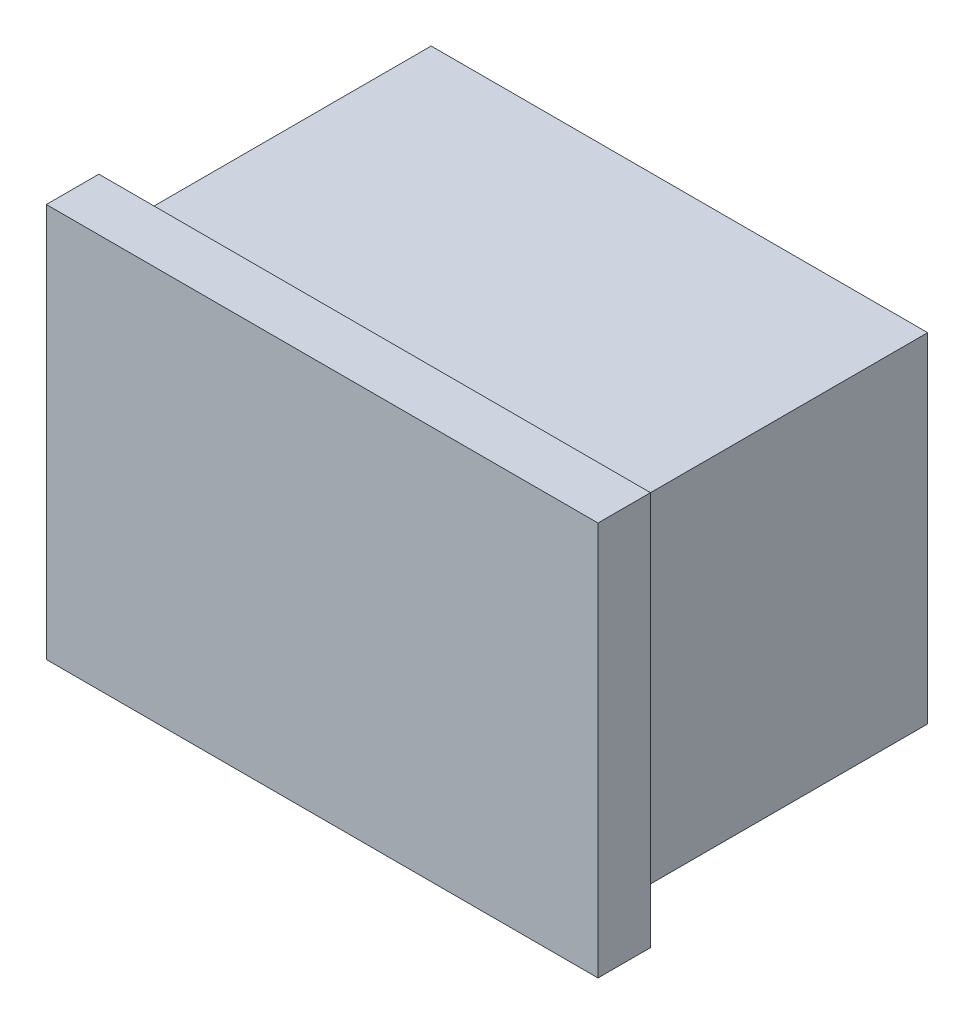
SolidWorks part; units mm, degrees
ref_plane "Front Plane" through (0, 0, 0) normal (0, 0, 1) x (1, 0, 0)
ref_plane "Top Plane" through (0, 0, 0) normal (0, 1, 0) x (1, 0, 0)
ref_plane "Right Plane" through (0, 0, 0) normal (1, 0, 0) x (0, 0, -1)
sketch "Sketch1" plane through (0, 0, 0) normal (0, 0, 1) x (1, 0, 0)
  line L1 (0, 0) -> (18.9, 0)
  line L2 (0, 0) -> (0, 12.9)
  line L3 (0, 12.9) -> (18.9, 12.9)
  line L4 (18.9, 0) -> (18.9, 12.9)
  dimension "D1" = 18.9
  dimension "D2" = 12.9
extrude "Boss-Extrude1" add sketch "Sketch1" along normal blind 11.6
sketch "Sketch2" plane through (0, 0, 11.6) normal (0, 0, 1) x (1, 0, 0)
  line L0 (18.9, 0) -> (18.9, 12.9) construction
  line L1 (19.95, 13.95) -> (-1.05, 13.95)
  line L2 (19.95, 13.95) -> (19.95, -1.05)
  line L3 (19.95, -1.05) -> (-1.05, -1.05)
  line L4 (-1.05, 13.95) -> (-1.05, -1.05)
  line L5 (0, 0) -> (18.9, 0) construction
  point P4 (19.95, 6.45)
  point P7 (18.9, 6.45)
  point P8 (9.45, -1.05)
  point P11 (9.45, 0)
  dimension "D1" = 21
  dimension "D2" = 15
extrude "Boss-Extrude2" add sketch "Sketch2" along normal blind 2
